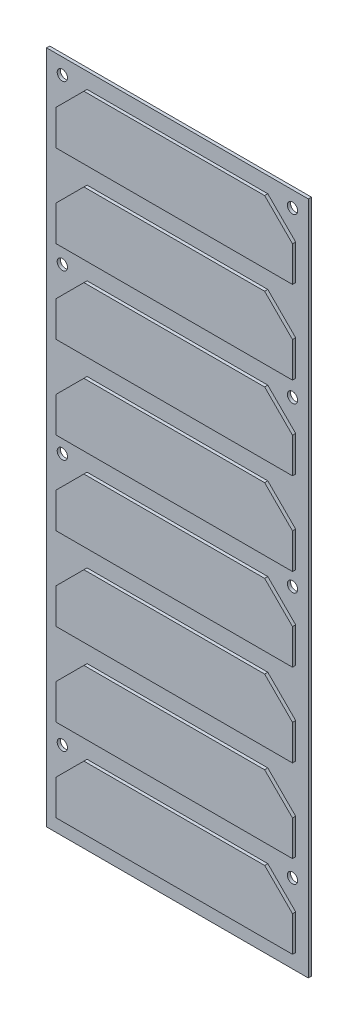
SolidWorks part; units mm, degrees
ref_plane "Front Plane" through (0, 0, 0) normal (0, 0, 1) x (1, 0, 0)
ref_plane "Top Plane" through (0, 0, 0) normal (0, 1, 0) x (1, 0, 0)
ref_plane "Right Plane" through (0, 0, 0) normal (1, 0, 0) x (0, 0, -1)
sketch "Sketch1" plane through (0, 0, 0) normal (0, 0, 1) x (1, 0, 0)
  line L1 (-41.5, -107) -> (41.5, -107)
  line L2 (-41.5, -107) -> (-41.5, 107)
  line L3 (-41.5, 107) -> (41.5, 107)
  line L4 (41.5, -107) -> (41.5, 107)
  line L5 (-41.5, -107) -> (41.5, 107) construction
  line L6 (-41.5, 107) -> (41.5, -107) construction
  point P0 (0, 0)
  dimension "D1" = 83
  dimension "D2" = 214
extrude "Boss-Extrude1" add sketch "Sketch1" along normal blind 1
sketch "Sketch2" plane through (0, 0, 1) normal (0, 0, 1) x (1, 0, 0)
  line L0 (-28.6612, 102) -> (28.6612, 102)
  line L1 (28.6612, 102) -> (37.5, 93.1612)
  line L2 (37.5, 93.1612) -> (37.5, 82)
  line L3 (37.5, 82) -> (-37.5, 82)
  line L4 (-37.5, 82) -> (-37.5, 93.1612)
  line L5 (-37.5, 93.1612) -> (-28.6612, 102)
  line L6 (0, 0) -> (0, 107) construction
  line L7 (41.5, 107) -> (-41.5, 107) construction
  line L8 (-28.6612, 75.7143) -> (28.6612, 75.7143)
  line L9 (28.6612, 75.7143) -> (37.5, 66.8755)
  line L10 (37.5, 66.8755) -> (37.5, 55.7143)
  line L11 (37.5, 55.7143) -> (-37.5, 55.7143)
  line L12 (-37.5, 55.7143) -> (-37.5, 66.8755)
  line L13 (-37.5, 66.8755) -> (-28.6612, 75.7143)
  line L14 (-28.6612, 49.4286) -> (28.6612, 49.4286)
  line L15 (28.6612, 49.4286) -> (37.5, 40.5897)
  line L16 (37.5, 40.5897) -> (37.5, 29.4286)
  line L17 (37.5, 29.4286) -> (-37.5, 29.4286)
  line L18 (-37.5, 29.4286) -> (-37.5, 40.5897)
  line L19 (-37.5, 40.5897) -> (-28.6612, 49.4286)
  line L20 (-28.6612, 23.1429) -> (28.6612, 23.1429)
  line L21 (28.6612, 23.1429) -> (37.5, 14.304)
  line L22 (37.5, 14.304) -> (37.5, 3.1429)
  line L23 (37.5, 3.1429) -> (-37.5, 3.1429)
  line L24 (-37.5, 3.1429) -> (-37.5, 14.304)
  line L25 (-37.5, 14.304) -> (-28.6612, 23.1429)
  line L26 (-28.6612, -3.1429) -> (28.6612, -3.1429)
  line L27 (28.6612, -3.1429) -> (37.5, -11.9817)
  line L28 (37.5, -11.9817) -> (37.5, -23.1429)
  line L29 (37.5, -23.1429) -> (-37.5, -23.1429)
  line L30 (-37.5, -23.1429) -> (-37.5, -11.9817)
  line L31 (-37.5, -11.9817) -> (-28.6612, -3.1429)
  line L32 (-28.6612, -29.4286) -> (28.6612, -29.4286)
  line L33 (28.6612, -29.4286) -> (37.5, -38.2674)
  line L34 (37.5, -38.2674) -> (37.5, -49.4286)
  line L35 (37.5, -49.4286) -> (-37.5, -49.4286)
  line L36 (-37.5, -49.4286) -> (-37.5, -38.2674)
  line L37 (-37.5, -38.2674) -> (-28.6612, -29.4286)
  line L38 (-28.6612, -55.7143) -> (28.6612, -55.7143)
  line L39 (28.6612, -55.7143) -> (37.5, -64.5531)
  line L40 (37.5, -64.5531) -> (37.5, -75.7143)
  line L41 (37.5, -75.7143) -> (-37.5, -75.7143)
  line L42 (-37.5, -75.7143) -> (-37.5, -64.5531)
  line L43 (-37.5, -64.5531) -> (-28.6612, -55.7143)
  line L44 (-28.6612, -82) -> (28.6612, -82)
  line L45 (28.6612, -82) -> (37.5, -90.8388)
  line L46 (37.5, -90.8388) -> (37.5, -102)
  line L47 (37.5, -102) -> (-37.5, -102)
  line L48 (-37.5, -102) -> (-37.5, -90.8388)
  line L49 (-37.5, -90.8388) -> (-28.6612, -82)
  line L50 (-41.5, -107) -> (41.5, -107) construction
  dimension "D1" = 75
  dimension "D2" = 20
  dimension "D3" = 45
  dimension "D4" = 12.5
  dimension "D5" = 5
  dimension "D7" = 5
  dimension "D6" = 8
extrude "Boss-Extrude2" add sketch "Sketch2" along normal blind 1
hole_wizard "#4 Clearance Hole1" positions "Sketch4" profile "Sketch3" hole size "#4" standard "ANSI Inch"
sketch "Sketch4" plane through (0, 0, 1) normal (0, 0, 1) x (1, 0, 0)
  line L0 (41.5, 107) -> (-41.5, 107) construction
  line L1 (-41.5, 107) -> (-41.5, -107) construction
  line L2 (41.5, -107) -> (41.5, 107) construction
  line L3 (-41.5, -107) -> (41.5, -107) construction
  point P0 (-36.5, 102)
  point P2 (36.5, 102)
  point P4 (36.5, 50)
  point P6 (36.5, -2)
  point P8 (36.5, -82)
  point P10 (-36.5, -82)
  point P12 (-36.5, -2)
  point P14 (-36.5, 50)
  dimension "D1" = 5
  dimension "D2" = 5
  dimension "D3" = 5
  dimension "D4" = 25
  dimension "D5" = 52
  dimension "D6" = 52
sketch "Sketch3" plane through (-36.5, 102, 1) normal (1, 0, 0) x (0, -1, 0)
  line L0 (0, 0) -> (0, 4.1556)
  line L1 (0, 4.1556) -> (1.6319, 3.175)
  line L2 (1.6319, 3.175) -> (1.6319, 0)
  line L5 (1.6319, 0) -> (0, 0)
  line L10 (0, 4.1556) -> (-1.632, 3.175) construction
  line L11 (0, -6.35) -> (0, 107.95) construction
  dimension "Hole Dia." = 3.2639
  dimension "Hole Depth" = 3.175
  dimension "Drill Angle" = 118
